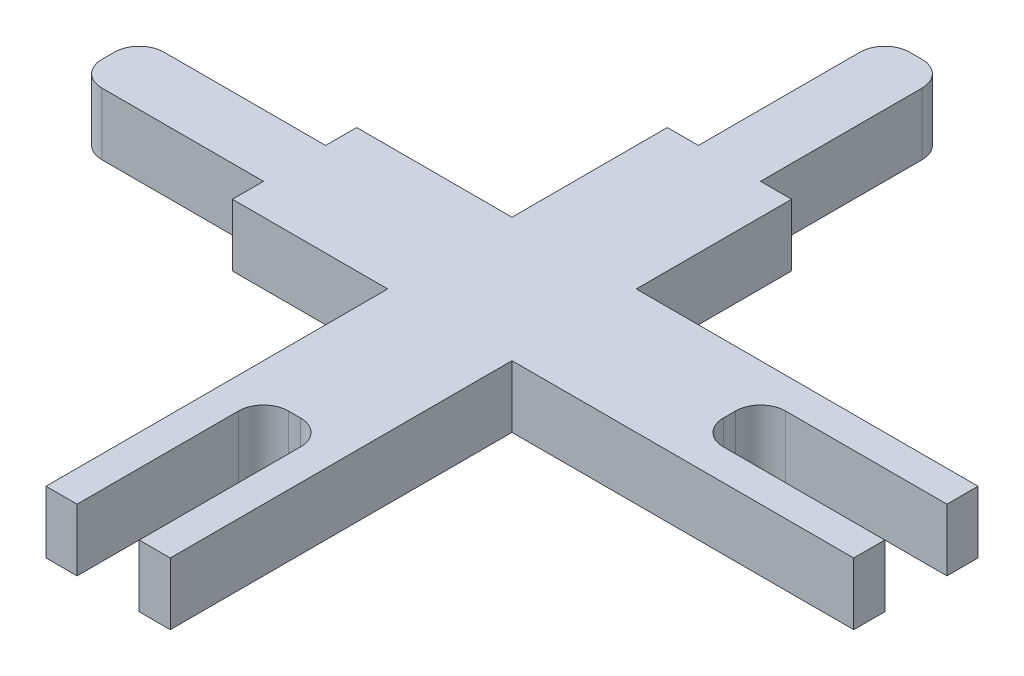
SolidWorks part; units mm, degrees
ref_plane "Alzado" through (0, 0, 0) normal (0, 0, 1) x (1, 0, 0)
ref_plane "Planta" through (0, 0, 0) normal (0, 1, 0) x (1, 0, 0)
ref_plane "Vista lateral" through (0, 0, 0) normal (1, 0, 0) x (0, 0, -1)
sketch "Croquis1" plane through (0, 0, 0) normal (0, 1, 0) x (1, 0, 0)
  line L1 (0, 0) -> (50, 0)
  line L2 (0, 0) -> (0, 10)
  line L3 (0, 10) -> (50, 10)
  line L4 (50, 0) -> (50, 10)
  dimension "D1" = 10
  dimension "D2" = 50
extrude "Saliente-Extruir1" add sketch "Croquis1" along normal mid plane 5
sketch "Croquis2" plane through (0, 2.5, 0) normal (0, 1, 0) x (1, 0, 0)
  line L0 (50, 0) -> (50, 10) construction
  line L1 (50, 7.5) -> (37, 7.5)
  line L2 (50, 7.5) -> (50, 2.5)
  line L3 (50, 2.5) -> (37, 2.5)
  line L4 (35, 5.5) -> (35, 4.5)
  line L5 (0, 5) -> (88.2165, 5) construction
  line L6 (0, 10) -> (0, 0) construction
  arc A0 (37, 2.5) -> (35, 4.5) centre (37, 4.5) cw
  arc A1 (37, 7.5) -> (35, 5.5) centre (37, 5.5) ccw
  point P10 (35, 5)
  point P15 (35, 7.5)
  dimension "D3" = 2
  dimension "D1" = 5
  dimension "D2" = 15
extrude "Cortar-Extruir1" cut sketch "Croquis2" against normal through all
sketch "Croquis3" plane through (0, 2.5, 0) normal (0, 1, 0) x (1, 0, 0)
  line L0 (0, 10) -> (0, 0) construction
  line L1 (0, 2.5) -> (-13, 2.5)
  line L2 (0, 2.5) -> (0, 7.5)
  line L3 (0, 7.5) -> (-13, 7.5)
  line L4 (-15, 4.5) -> (-15, 5.5)
  arc A0 (-13, 2.5) -> (-15, 4.5) centre (-13, 4.5) cw
  arc A1 (-13, 7.5) -> (-15, 5.5) centre (-13, 5.5) ccw
  point P6 (0, 5)
  point P7 (0, 5)
  point P10 (-15, 2.5)
  point P13 (-15, 7.5)
  dimension "D3" = 2
  dimension "D1" = 15
  dimension "D2" = 5
extrude "Saliente-Extruir2" add sketch "Croquis3" against normal blind 5
sketch "Croquis4" plane through (0, 2.5, 0) normal (0, 1, 0) x (1, 0, 0)
  line L0 (-15, 5) -> (50, 5) construction
  line L1 (-15, 5.5) -> (-15, 4.5) construction
  line L2 (17.5, -27.5) -> (17.5, 37.5) construction
  line L3 (17, 37.5) -> (18, 37.5)
  line L4 (20, 35.5) -> (20, 22.5)
  line L5 (20, 22.5) -> (22.5, 22.5)
  line L6 (22.5, 22.5) -> (22.5, -27.5)
  line L7 (22.5, -27.5) -> (20, -27.5)
  line L8 (20, -27.5) -> (20, -14.5)
  line L9 (18, -12.5) -> (17, -12.5)
  line L10 (15, -14.5) -> (15, -27.5)
  line L11 (15, -27.5) -> (12.5, -27.5)
  line L12 (12.5, -27.5) -> (12.5, 22.5)
  line L13 (12.5, 22.5) -> (15, 22.5)
  line L14 (15, 22.5) -> (15, 35.5)
  arc A0 (20, -14.5) -> (18, -12.5) centre (18, -14.5) ccw
  arc A1 (17, -12.5) -> (15, -14.5) centre (17, -14.5) ccw
  arc A2 (18, 37.5) -> (20, 35.5) centre (18, 35.5) cw
  arc A3 (17, 37.5) -> (15, 35.5) centre (17, 35.5) ccw
  point P7 (17.5, 5)
  point P9 (0, 0)
  point P20 (0, 0)
  point P21 (0, 0)
  point P22 (0, 0)
  point P23 (17.5, 37.5)
  point P24 (17.5, -12.5)
  point P25 (0, 0)
  point P29 (20, -12.5)
  point P32 (15, -12.5)
  point P35 (20, 37.5)
  point P38 (15, 37.5)
  dimension "D6" = 2
  dimension "D1" = 65
  dimension "D2" = 15
  dimension "D3" = 15
  dimension "D4" = 10
  dimension "D5" = 5
extrude "Saliente-Extruir3" add sketch "Croquis4" against normal blind 5
